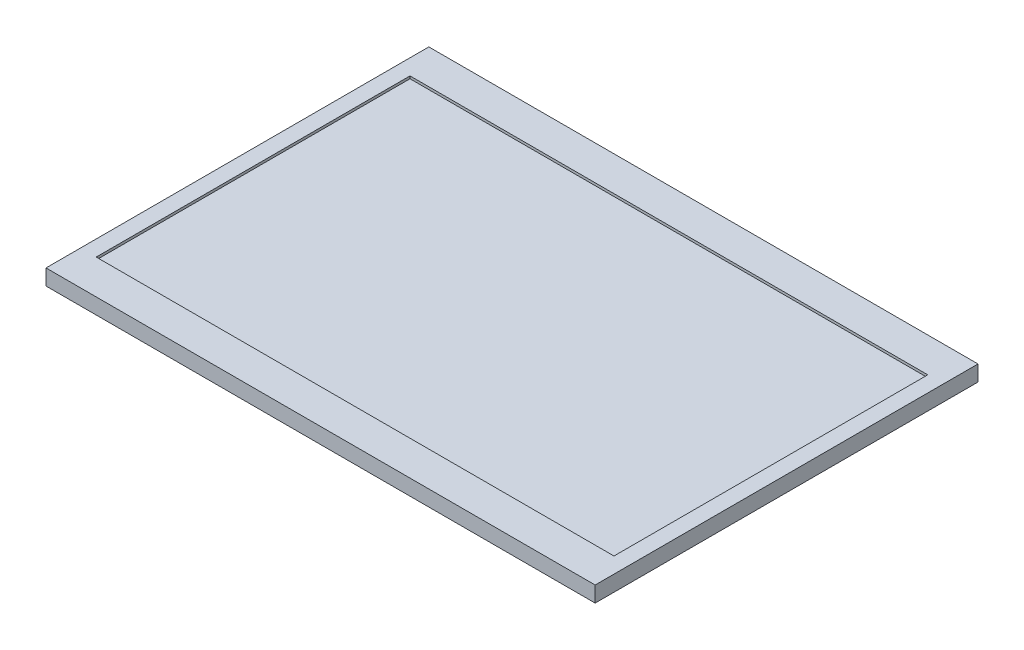
SolidWorks part; units mm, degrees
ref_plane "Front Plane" through (0, 0, 0) normal (0, 0, 1) x (1, 0, 0)
ref_plane "Top Plane" through (0, 0, 0) normal (0, 1, 0) x (1, 0, 0)
ref_plane "Right Plane" through (0, 0, 0) normal (1, 0, 0) x (0, 0, -1)
sketch "Croquis1" plane through (0, 0, 0) normal (0, 1, 0) x (1, 0, 0)
  line L0 (0, 0) -> (0, 55) construction
  line L1 (0, 0) -> (47.6314, -27.5) construction
  line L2 (0, 0) -> (-47.6314, -27.5) construction
  line L4 (15, -25.9808) -> (30, 0)
  line L5 (30, 0) -> (15, 25.9808)
  line L6 (15, 25.9808) -> (-15, 25.9808)
  line L7 (-15, 25.9808) -> (-30, 0)
  line L8 (-30, 0) -> (-15, -25.9808)
  line L9 (-15, 61) -> (-15, 9.0139)
  line L10 (-5, 61) -> (-5, 16.7705)
  line L11 (5, 16.7705) -> (5, 61)
  line L12 (15, 9.0139) -> (15, 61)
  line L13 (-15, 61) -> (-5, 61)
  line L14 (15, 61) -> (5, 61)
  line L15 (-15, 49) -> (15, 49)
  line L16 (-15, 44) -> (15, 44)
  line L17 (60.3275, -17.5096) -> (15.3062, 8.4834)
  line L18 (55.3275, -26.1699) -> (17.0237, -4.0551)
  line L19 (60.3275, -17.5096) -> (55.3275, -26.1699)
  line L20 (49.9352, -11.5096) -> (34.9352, -37.4904)
  line L21 (45.6051, -9.0096) -> (30.6051, -34.9904)
  line L22 (12.0237, -12.7154) -> (50.3275, -34.8301)
  line L23 (45.3275, -43.4904) -> (50.3275, -34.8301)
  line L24 (0.3062, -17.4973) -> (45.3275, -43.4904)
  line L25 (-45.3275, -43.4904) -> (-0.3062, -17.4973)
  line L26 (-50.3275, -34.8301) -> (-12.0237, -12.7154)
  line L27 (-45.3275, -43.4904) -> (-50.3275, -34.8301)
  line L28 (-34.9352, -37.4904) -> (-49.9352, -11.5096)
  line L29 (-30.6051, -34.9904) -> (-45.6051, -9.0096)
  line L30 (-17.0237, -4.0551) -> (-55.3275, -26.1699)
  line L31 (-60.3275, -17.5096) -> (-55.3275, -26.1699)
  line L32 (-15.3062, 8.4834) -> (-60.3275, -17.5096)
  line L33 (-15, -25.9808) -> (15, -25.9808)
  line L34 (10.1036, -17.5) -> (20.2073, 0)
  line L35 (20.2073, 0) -> (10.1036, 17.5)
  line L36 (10.1036, 17.5) -> (-10.1036, 17.5)
  line L37 (-10.1036, 17.5) -> (-20.2073, 0)
  line L38 (-20.2073, 0) -> (-10.1036, -17.5)
  line L39 (-10.1036, -17.5) -> (10.1036, -17.5)
  circle A0 centre (0, 0) radius 17.5 construction
  circle A1 centre (0, 0) radius 25.9808 construction
  circle A2 centre (0, 0) radius 25.9808 construction
  circle A3 centre (0, 0) radius 17.5 construction
  point P4 (17.0237, -32.4904)
  point P7 (0, 0)
  point P59 (0, 0)
  dimension "D7" = 35
  dimension "D1" = 55
  dimension "D9" = 10
  dimension "D11" = 6
  dimension "D10" = 10
  dimension "D12" = 6
  dimension "D13" = 5
  dimension "D14" = 3
  dimension "D3" = 10
  dimension "D4" = 5
  dimension "D2" = 3
extrude "Saliente-Extruir1" add sketch "Croquis1" along normal blind 12 contours L9 A1 L32 A0 | L32 A1 L30 A0 | A1 L32 L29 L30 | L29 L32 L28 L30 | L28 L32 L31 L30 | L29 L30 L28 L26 | L25 L28 L26 L27 | L25 L29 L26 L28 | A1 L26 L29 L25 | L26 A1 L25 A0 | L25 A1 L24 A0 | L24 A1 L22 A0 | A1 L24 L21 L22 | L21 L24 L20 L22 | L20 L24 L23 L22 | L17 L20 L18 L19 | L21 L22 L20 L18 | L17 L21 L18 L20 | L18 A1 L17 A0 | A1 L18 L21 L17 | L17 A1 L12 A0 | L12 A1 L11 A0 | L10 A1 L9 A0 | A1 L12 L16 L11 | L11 L16 L12 L15 | L11 L15 L12 L14 | L10 L16 L11 L15 | A1 L10 L16 L9 | L9 L16 L10 L15 | L9 L15 L10 L13 | L38 L30 L8 L26 | L34 L22 L4 L18 | L36 L11 L6 L10
sketch "Croquis2" plane through (-15, 0, 0) normal (-1, 0, 0) x (0, 0, 1)
  line L0 (-61, 12) -> (-25.9808, 12) construction
  line L1 (-61, 12) -> (-61, 0) construction
  circle A0 centre (-55, 5) radius 1.55
  dimension "D1" = 3.1
  dimension "D2" = 6
  dimension "D3" = 7
sketch "Croquis3" plane through (7.5, 0, 12.9904) normal (0.5, 0, 0.866) x (0.866, 0, -0.5)
  line L0 (-61, 0) -> (-25.9808, 0) construction
  line L1 (-61, 12) -> (-61, 0) construction
  circle A0 centre (-55, 5) radius 1.55
  dimension "D1" = 3.1
  dimension "D2" = 5
  dimension "D3" = 6
sketch "Croquis4" plane through (7.5, 0, -12.9904) normal (0.5, 0, -0.866) x (-0.866, 0, -0.5)
  line L0 (-61, 0) -> (-25.9808, 0) construction
  line L1 (-61, 12) -> (-61, 0) construction
  circle A0 centre (-55, 5) radius 1.55
  dimension "D1" = 5
  dimension "D3" = 3.1
  dimension "D2" = 6
extrude "Cortar-Extruir1" cut sketch "Croquis2" against normal up to surface (30 mm away) up to face at (15, 6, -43.4904)
extrude "Cortar-Extruir2" cut sketch "Croquis3" against normal up to surface (30 mm away) up to face at (-45.1638, 6, 8.7548)
extrude "Cortar-Extruir3" cut sketch "Croquis4" against normal up to surface (30 mm away) up to face at (30.1638, 6, 34.7356)
sketch "Croquis6" plane through (0, 12, 0) normal (0, 1, 0) x (1, 0, 0)
  line L0 (-87.5, 61) -> (87.5, 61)
  line L1 (-87.5, 61) -> (-87.5, -61)
  line L2 (87.5, 61) -> (87.5, -61)
  line L3 (-87.5, -61) -> (87.5, -61)
  point P0 (0, -61)
  point P3 (87.5, 0)
  point P5 (0, 0)
  dimension "D1" = 175
  dimension "D2" = 122
extrude "Saliente-Extruir7" add sketch "Croquis6" along normal blind 5
fillet "Redondeo1" radius 2 12 edges at (-35.6051, 6, 26.3301) (-40.6051, 6, 17.6699) (40.6051, 6, 17.6699) (35.6051, 6, 26.3301) (5, 6, -44) (-5, 6, -44) (25, 6, 8.6603) (20, 6, 17.3205) (-5, 6, -25.9808) (5, 6, -25.9808) (-25, 6, 8.6603) (-20, 6, 17.3205)
fillet "Redondeo2" radius 1 18 edges at (-39.9352, 6, 28.8301) (-60.3275, 6, 17.5096) (-50.3275, 6, 34.8301) (-45.3275, 6, 43.4904) (-55.3275, 6, 26.1699) (-44.9352, 6, 20.1699) (39.9352, 6, 28.8301) (45.3275, 6, 43.4904) (55.3275, 6, 26.1699) (44.9352, 6, 20.1699) (50.3275, 6, 34.8301) (60.3275, 6, 17.5096) (5, 6, -49) (-15, 6, -61) (15, 6, -61) (5, 6, -61) (-5, 6, -61) (-5, 6, -49)
sketch "Croquis7" plane through (0, 17, 0) normal (0, 1, 0) x (1, 0, 0)
  line L1 (-82.5, 50) -> (82.5, 50)
  line L2 (-82.5, 50) -> (-82.5, -50)
  line L3 (-82.5, -50) -> (82.5, -50)
  line L4 (82.5, 50) -> (82.5, -50)
  line L5 (-82.5, 50) -> (82.5, -50) construction
  line L6 (-82.5, -50) -> (82.5, 50) construction
  point P0 (0, 0)
  dimension "D1" = 165
  dimension "D2" = 100
extrude "Cortar-Extruir4" cut sketch "Croquis7" against normal blind 0.8
equation "\"A\"=5.0321"
